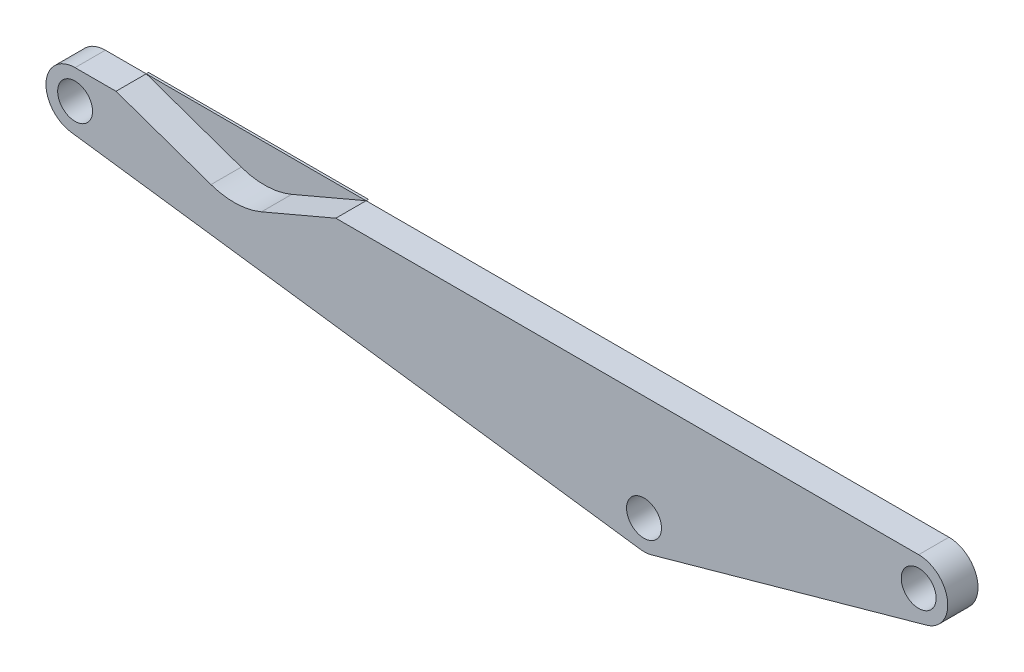
SolidWorks part; units mm, degrees
ref_plane "前基準面" through (0, 0, 0) normal (0, 0, 1) x (1, 0, 0)
ref_plane "上基準面" through (0, 0, 0) normal (0, 1, 0) x (1, 0, 0)
ref_plane "右基準面" through (0, 0, 0) normal (1, 0, 0) x (0, 0, -1)
sketch "草圖1" plane through (0, 0, 0) normal (0, 0, 1) x (1, 0, 0)
  line L0 (0, 0) -> (36.24, 0) construction
  line L1 (36.24, 0) -> (24.4397, -3.2887) construction
  line L2 (24.4397, -3.2887) -> (0, 0) construction
  line L3 (0, 1.25) -> (36.24, 1.25)
  line L4 (-0.1667, -1.2388) -> (24.273, -4.5276)
  line L5 (24.7753, -4.4929) -> (36.5756, -1.2041)
  arc A0 (0, 1.25) -> (-0.1667, -1.2388) centre (0, 0) ccw
  arc A1 (36.5756, -1.2041) -> (36.24, 1.25) centre (36.24, 0) ccw
  arc A2 (24.273, -4.5276) -> (24.7753, -4.4929) centre (24.4397, -3.2887) ccw
  circle A3 centre (0, 0) radius 0.75
  circle A4 centre (36.24, 0) radius 0.75
  circle A5 centre (24.4397, -3.2887) radius 0.75
  dimension "D3" = 2.5
  dimension "D5" = 1.5
  dimension "D1" = 12.25
  dimension "D2" = 24.66
  dimension "D4" = 36.24
extrude "填料-伸長1" add sketch "草圖1" along normal mid plane 1.3
sketch "草圖2" plane through (0, 0, 0.65) normal (0, 0, 1) x (1, 0, 0)
  line L0 (1.7573, 1.25) -> (5.8371, -0.1819)
  line L1 (36.24, 1.25) -> (0, 1.25) construction
  line L2 (8.0062, -0.1112) -> (11.2021, 1.25)
  line L3 (1.7573, 1.25) -> (11.2021, 1.25)
  arc A0 (5.8371, -0.1819) -> (8.0062, -0.1112) centre (6.8306, 2.6488) ccw
  dimension "D1" = 3
extrude "除料-伸長1" cut sketch "草圖2" against normal blind 10
sketch "草圖3" plane through (0, 0, 0.65) normal (0, 0, 1) x (1, 0, 0)
  line L2 (1.7573, 1.25) -> (0, 1.25) construction
  line L3 (-0.1667, -1.2388) -> (24.273, -4.5276) construction
  line L6 (1.7573, 1.25) -> (5.8371, -0.1819) construction
  line L7 (8.0062, -0.1112) -> (11.2021, 1.25) construction
  line L8 (-0.1667, -1.2388) -> (12.0532, -2.8832)
  line L9 (1.7573, 1.25) -> (0, 1.25)
  line L10 (1.7573, 1.25) -> (5.8371, -0.1819)
  line L11 (8.0062, -0.1112) -> (11.2021, 1.25)
  line L12 (11.2021, 1.25) -> (12.0532, -2.8832)
  arc A2 (0, 1.25) -> (-0.1667, -1.2388) centre (0, 0) ccw construction
  circle A5 centre (0, 0) radius 0.75 construction
  arc A6 (5.8371, -0.1819) -> (8.0062, -0.1112) centre (6.8306, 2.6488) ccw construction
  circle A7 centre (0, 0) radius 0.75
  arc A8 (0, 1.25) -> (-0.1667, -1.2388) centre (0, 0) ccw
  arc A9 (5.8371, -0.1819) -> (8.0062, -0.1112) centre (6.8306, 2.6488) ccw
sketch "草圖4" plane through (0, 0, -0.65) normal (0, 0, -1) x (-1, 0, 0)
  line L0 (-1.7573, 1.25) -> (-11.2021, 1.25) construction
  line L1 (-8.0062, -0.1112) -> (-11.2021, 1.25) construction
  line L2 (-1.7573, 1.25) -> (-5.8371, -0.1819) construction
  line L3 (-8.0062, -0.1112) -> (-11.2021, 1.25)
  line L4 (-1.7573, 1.25) -> (-5.8371, -0.1819)
  line L5 (-1.7573, 1.25) -> (-11.2021, 1.25)
  arc A0 (-8.0062, -0.1112) -> (-5.8371, -0.1819) centre (-6.8306, 2.6488) ccw construction
  arc A1 (-8.0062, -0.1112) -> (-5.8371, -0.1819) centre (-6.8306, 2.6488) ccw
extrude "填料-伸長3" add sketch "草圖4" along normal blind 0.1 separate body
